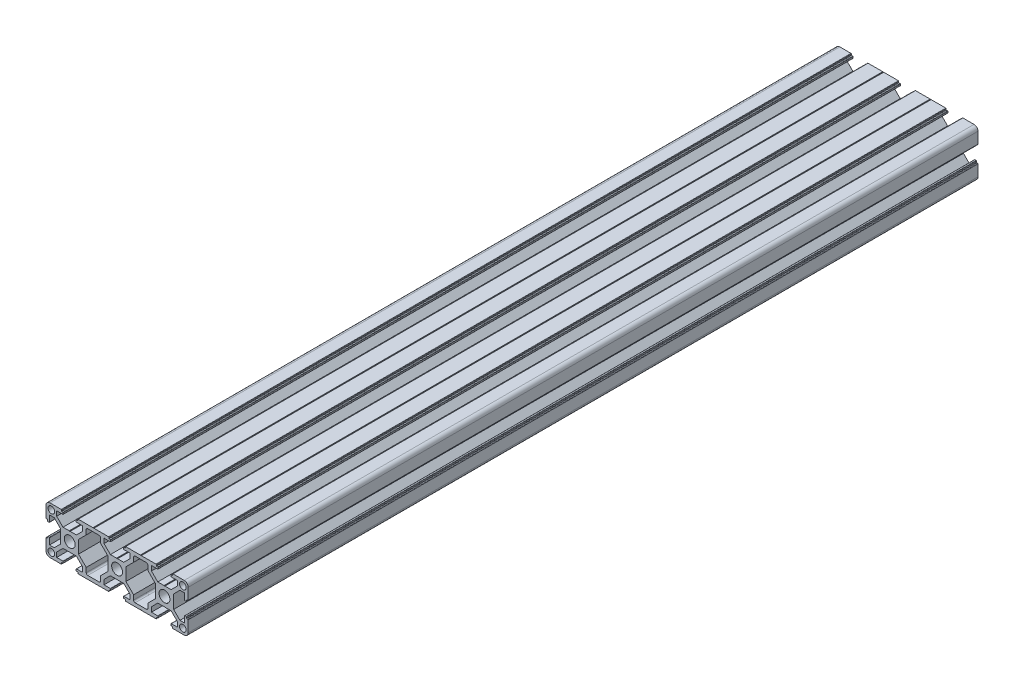
SolidWorks part; units mm, degrees
material "6063-T5"
ref_plane "Спереди" through (0, 0, 0) normal (0, 0, 1) x (1, 0, 0)
ref_plane "Сверху" through (0, 0, 0) normal (0, 1, 0) x (1, 0, 0)
ref_plane "Справа" through (0, 0, 0) normal (1, 0, 0) x (0, 0, -1)
sketch "Эскиз1" plane through (0, 500, 0) normal (0, 0, -1) x (1, 0, 0)
  line L0 (-18.55, 12.8) -> (-11.45, 12.8)
  line L1 (-10.45, 11.8) -> (-10.45, 8.8944)
  line L2 (-10.45, 8.8944) -> (-5.6, 4.0444)
  line L3 (-5.6, 4.0444) -> (-5.6, -4.0444)
  line L4 (-5.6, -4.0444) -> (-10.45, -8.8944)
  line L5 (-10.45, -8.8944) -> (-10.45, -11.8)
  line L6 (-11.45, -12.8) -> (-18.55, -12.8)
  line L7 (-19.55, -11.8) -> (-19.55, -8.8944)
  line L8 (-19.55, -8.8944) -> (-24.4, -4.0444)
  line L9 (-24.4, -4.0444) -> (-24.4, 4.0444)
  line L10 (-24.4, 4.0444) -> (-19.55, 8.8944)
  line L11 (-19.55, 8.8944) -> (-19.55, 11.8)
  line L12 (19.55, 11.8) -> (19.55, 8.8944)
  line L13 (19.55, 8.8944) -> (24.4, 4.0444)
  line L14 (24.4, 4.0444) -> (24.4, -4.0444)
  line L15 (24.4, -4.0444) -> (19.55, -8.8944)
  line L16 (19.55, -8.8944) -> (19.55, -11.8)
  line L17 (18.55, -12.8) -> (11.45, -12.8)
  line L18 (10.45, -11.8) -> (10.45, -8.8944)
  line L19 (10.45, -8.8944) -> (5.6, -4.0444)
  line L20 (5.6, -4.0444) -> (5.6, 4.0444)
  line L21 (5.6, 4.0444) -> (10.45, 8.8944)
  line L22 (10.45, 8.8944) -> (10.45, 11.8)
  line L23 (11.45, 12.8) -> (18.55, 12.8)
  line L24 (15.3377, -15) -> (24.6, -15)
  line L25 (24.8, -14.8) -> (24.8, -14.2)
  line L26 (25, -14) -> (25.7, -14)
  line L27 (25.9, -13.8) -> (25.9, -13)
  line L28 (25.7, -12.8) -> (21.75, -12.8)
  line L29 (21.75, -12.8) -> (21.75, -9.8056)
  line L30 (21.75, -9.8056) -> (25.7556, -5.8)
  line L31 (25.7556, -5.8) -> (29.6623, -5.8)
  line L32 (29.8185, -5.7452) -> (30, -5.6)
  line L33 (30, -5.6) -> (30.1815, -5.7452)
  line L34 (30.3377, -5.8) -> (34.2444, -5.8)
  line L35 (34.2444, -5.8) -> (38.25, -9.8056)
  line L36 (38.25, -9.8056) -> (38.25, -12.8)
  line L37 (38.25, -12.8) -> (34.3, -12.8)
  line L38 (34.1, -13) -> (34.1, -13.8)
  line L39 (34.3, -14) -> (35, -14)
  line L40 (35.2, -14.2) -> (35.2, -14.8)
  line L41 (35.4, -15) -> (42.5, -15)
  line L42 (45, -12.5) -> (45, -5.4)
  line L43 (44.8, -5.2) -> (44.2, -5.2)
  line L44 (44, -5) -> (44, -4.3)
  line L45 (43.8, -4.1) -> (43, -4.1)
  line L46 (42.8, -4.3) -> (42.8, -8.25)
  line L47 (42.8, -8.25) -> (39.8056, -8.25)
  line L48 (39.8056, -8.25) -> (35.8, -4.2444)
  line L49 (35.8, -4.2444) -> (35.8, 4.2444)
  line L50 (35.8, 4.2444) -> (39.8056, 8.25)
  line L51 (39.8056, 8.25) -> (42.8, 8.25)
  line L52 (42.8, 8.25) -> (42.8, 4.3)
  line L53 (43, 4.1) -> (43.8, 4.1)
  line L54 (44, 4.3) -> (44, 5)
  line L55 (44.2, 5.2) -> (44.8, 5.2)
  line L56 (45, 5.4) -> (45, 12.5)
  line L57 (42.5, 15) -> (35.4, 15)
  line L58 (35.2, 14.8) -> (35.2, 14.2)
  line L59 (35, 14) -> (34.3, 14)
  line L60 (34.1, 13.8) -> (34.1, 13)
  line L61 (34.3, 12.8) -> (38.25, 12.8)
  line L62 (38.25, 12.8) -> (38.25, 9.8056)
  line L63 (38.25, 9.8056) -> (34.2444, 5.8)
  line L64 (34.2444, 5.8) -> (30.3377, 5.8)
  line L65 (30.1815, 5.7452) -> (30, 5.6)
  line L66 (30, 5.6) -> (29.8185, 5.7452)
  line L67 (29.6623, 5.8) -> (25.7556, 5.8)
  line L68 (25.7556, 5.8) -> (21.75, 9.8056)
  line L69 (21.75, 9.8056) -> (21.75, 12.8)
  line L70 (21.75, 12.8) -> (25.7, 12.8)
  line L71 (25.9, 13) -> (25.9, 13.8)
  line L72 (25.7, 14) -> (25, 14)
  line L73 (24.8, 14.2) -> (24.8, 14.8)
  line L74 (24.6, 15) -> (15.3377, 15)
  line L75 (15.1815, 14.9452) -> (15, 14.8)
  line L76 (15, 14.8) -> (14.8185, 14.9452)
  line L77 (14.6623, 15) -> (5.4, 15)
  line L78 (5.2, 14.8) -> (5.2, 14.2)
  line L79 (5, 14) -> (4.3, 14)
  line L80 (4.1, 13.8) -> (4.1, 13)
  line L81 (4.3, 12.8) -> (8.25, 12.8)
  line L82 (8.25, 12.8) -> (8.25, 9.8056)
  line L83 (8.25, 9.8056) -> (4.2444, 5.8)
  line L84 (4.2444, 5.8) -> (0.3377, 5.8)
  line L85 (0.1815, 5.7452) -> (0, 5.6)
  line L86 (0, 5.6) -> (-0.1815, 5.7452)
  line L87 (-0.3377, 5.8) -> (-4.2444, 5.8)
  line L88 (-4.2444, 5.8) -> (-8.25, 9.8056)
  line L89 (-8.25, 9.8056) -> (-8.25, 12.8)
  line L90 (-8.25, 12.8) -> (-4.3, 12.8)
  line L91 (-4.1, 13) -> (-4.1, 13.8)
  line L92 (-4.3, 14) -> (-5, 14)
  line L93 (-5.2, 14.2) -> (-5.2, 14.8)
  line L94 (-5.4, 15) -> (-14.6623, 15)
  line L95 (-14.8185, 14.9452) -> (-15, 14.8)
  line L96 (-15, 14.8) -> (-15.1815, 14.9452)
  line L97 (-15.3377, 15) -> (-24.6, 15)
  line L98 (-24.8, 14.8) -> (-24.8, 14.2)
  line L99 (-25, 14) -> (-25.7, 14)
  line L100 (-25.9, 13.8) -> (-25.9, 13)
  line L101 (-25.7, 12.8) -> (-21.75, 12.8)
  line L102 (-21.75, 12.8) -> (-21.75, 9.8056)
  line L103 (-21.75, 9.8056) -> (-25.7556, 5.8)
  line L104 (-25.7556, 5.8) -> (-29.6623, 5.8)
  line L105 (-29.8185, 5.7452) -> (-30, 5.6)
  line L106 (-30, 5.6) -> (-30.1815, 5.7452)
  line L107 (-30.3377, 5.8) -> (-34.2444, 5.8)
  line L108 (-34.2444, 5.8) -> (-38.25, 9.8056)
  line L109 (-38.25, 9.8056) -> (-38.25, 12.8)
  line L110 (-38.25, 12.8) -> (-34.3, 12.8)
  line L111 (-34.1, 13) -> (-34.1, 13.8)
  line L112 (-34.3, 14) -> (-35, 14)
  line L113 (-35.2, 14.2) -> (-35.2, 14.8)
  line L114 (-35.4, 15) -> (-42.5, 15)
  line L115 (-45, 12.5) -> (-45, 5.4)
  line L116 (-44.8, 5.2) -> (-44.2, 5.2)
  line L117 (-44, 5) -> (-44, 4.3)
  line L118 (-43.8, 4.1) -> (-43, 4.1)
  line L119 (-42.8, 4.3) -> (-42.8, 8.25)
  line L120 (-42.8, 8.25) -> (-39.8056, 8.25)
  line L121 (-39.8056, 8.25) -> (-35.8, 4.2444)
  line L122 (-35.8, 4.2444) -> (-35.8, -4.2444)
  line L123 (-35.8, -4.2444) -> (-39.8056, -8.25)
  line L124 (-39.8056, -8.25) -> (-42.8, -8.25)
  line L125 (-42.8, -8.25) -> (-42.8, -4.3)
  line L126 (-43, -4.1) -> (-43.8, -4.1)
  line L127 (-44, -4.3) -> (-44, -5)
  line L128 (-44.2, -5.2) -> (-44.8, -5.2)
  line L129 (-45, -5.4) -> (-45, -12.5)
  line L130 (-42.5, -15) -> (-35.4, -15)
  line L131 (-35.2, -14.8) -> (-35.2, -14.2)
  line L132 (-35, -14) -> (-34.3, -14)
  line L133 (-34.1, -13.8) -> (-34.1, -13)
  line L134 (-34.3, -12.8) -> (-38.25, -12.8)
  line L135 (-38.25, -12.8) -> (-38.25, -9.8056)
  line L136 (-38.25, -9.8056) -> (-34.2444, -5.8)
  line L137 (-34.2444, -5.8) -> (-30.3377, -5.8)
  line L138 (-30.1815, -5.7452) -> (-30, -5.6)
  line L139 (-30, -5.6) -> (-29.8185, -5.7452)
  line L140 (-29.6623, -5.8) -> (-25.7556, -5.8)
  line L141 (-25.7556, -5.8) -> (-21.75, -9.8056)
  line L142 (-21.75, -9.8056) -> (-21.75, -12.8)
  line L143 (-21.75, -12.8) -> (-25.7, -12.8)
  line L144 (-25.9, -13) -> (-25.9, -13.8)
  line L145 (-25.7, -14) -> (-25, -14)
  line L146 (-24.8, -14.2) -> (-24.8, -14.8)
  line L147 (-24.6, -15) -> (-15.3377, -15)
  line L148 (-15.1815, -14.9452) -> (-15, -14.8)
  line L149 (-15, -14.8) -> (-14.8185, -14.9452)
  line L150 (-14.6623, -15) -> (-5.4, -15)
  line L151 (-5.2, -14.8) -> (-5.2, -14.2)
  line L152 (-5, -14) -> (-4.3, -14)
  line L153 (-4.1, -13.8) -> (-4.1, -13)
  line L154 (-4.3, -12.8) -> (-8.25, -12.8)
  line L155 (-8.25, -12.8) -> (-8.25, -9.8056)
  line L156 (-8.25, -9.8056) -> (-4.2444, -5.8)
  line L157 (-4.2444, -5.8) -> (-0.3377, -5.8)
  line L158 (-0.1815, -5.7452) -> (0, -5.6)
  line L159 (0, -5.6) -> (0.1815, -5.7452)
  line L160 (0.3377, -5.8) -> (4.2444, -5.8)
  line L161 (4.2444, -5.8) -> (8.25, -9.8056)
  line L162 (8.25, -9.8056) -> (8.25, -12.8)
  line L163 (8.25, -12.8) -> (4.3, -12.8)
  line L164 (4.1, -13) -> (4.1, -13.8)
  line L165 (4.3, -14) -> (5, -14)
  line L166 (5.2, -14.2) -> (5.2, -14.8)
  line L167 (5.4, -15) -> (14.6623, -15)
  line L168 (14.8185, -14.9452) -> (15, -14.8)
  line L169 (15, -14.8) -> (15.1815, -14.9452)
  circle A0 centre (41.625, -11.625) radius 2.1
  circle A1 centre (41.625, 11.625) radius 2.1
  circle A2 centre (-41.625, 11.625) radius 2.1
  circle A3 centre (-41.625, -11.625) radius 2.1
  circle A4 centre (30, 0) radius 3.45
  circle A5 centre (-30, 0) radius 3.45
  circle A6 centre (0, 0) radius 3.45
  arc A7 (-11.45, 12.8) -> (-10.45, 11.8) centre (-11.45, 11.8) cw
  arc A8 (-10.45, -11.8) -> (-11.45, -12.8) centre (-11.45, -11.8) cw
  arc A9 (-18.55, -12.8) -> (-19.55, -11.8) centre (-18.55, -11.8) cw
  arc A10 (-19.55, 11.8) -> (-18.55, 12.8) centre (-18.55, 11.8) cw
  arc A11 (19.55, -11.8) -> (18.55, -12.8) centre (18.55, -11.8) cw
  arc A12 (11.45, -12.8) -> (10.45, -11.8) centre (11.45, -11.8) cw
  arc A13 (10.45, 11.8) -> (11.45, 12.8) centre (11.45, 11.8) cw
  arc A14 (18.55, 12.8) -> (19.55, 11.8) centre (18.55, 11.8) cw
  arc A15 (24.6, -15) -> (24.8, -14.8) centre (24.6, -14.8) ccw
  arc A16 (24.8, -14.2) -> (25, -14) centre (25, -14.2) cw
  arc A17 (25.7, -14) -> (25.9, -13.8) centre (25.7, -13.8) ccw
  arc A18 (25.9, -13) -> (25.7, -12.8) centre (25.7, -13) ccw
  arc A19 (29.6623, -5.8) -> (29.8185, -5.7452) centre (29.6623, -5.55) ccw
  arc A20 (30.1815, -5.7452) -> (30.3377, -5.8) centre (30.3377, -5.55) ccw
  arc A21 (34.3, -12.8) -> (34.1, -13) centre (34.3, -13) ccw
  arc A22 (34.1, -13.8) -> (34.3, -14) centre (34.3, -13.8) ccw
  arc A23 (35, -14) -> (35.2, -14.2) centre (35, -14.2) cw
  arc A24 (35.2, -14.8) -> (35.4, -15) centre (35.4, -14.8) ccw
  arc A25 (42.5, -15) -> (45, -12.5) centre (42.5, -12.5) ccw
  arc A26 (45, -5.4) -> (44.8, -5.2) centre (44.8, -5.4) ccw
  arc A27 (44.2, -5.2) -> (44, -5) centre (44.2, -5) cw
  arc A28 (44, -4.3) -> (43.8, -4.1) centre (43.8, -4.3) ccw
  arc A29 (43, -4.1) -> (42.8, -4.3) centre (43, -4.3) ccw
  arc A30 (42.8, 4.3) -> (43, 4.1) centre (43, 4.3) ccw
  arc A31 (43.8, 4.1) -> (44, 4.3) centre (43.8, 4.3) ccw
  arc A32 (44, 5) -> (44.2, 5.2) centre (44.2, 5) cw
  arc A33 (44.8, 5.2) -> (45, 5.4) centre (44.8, 5.4) ccw
  arc A34 (45, 12.5) -> (42.5, 15) centre (42.5, 12.5) ccw
  arc A35 (35.4, 15) -> (35.2, 14.8) centre (35.4, 14.8) ccw
  arc A36 (35.2, 14.2) -> (35, 14) centre (35, 14.2) cw
  arc A37 (34.3, 14) -> (34.1, 13.8) centre (34.3, 13.8) ccw
  arc A38 (34.1, 13) -> (34.3, 12.8) centre (34.3, 13) ccw
  arc A39 (30.3377, 5.8) -> (30.1815, 5.7452) centre (30.3377, 5.55) ccw
  arc A40 (29.8185, 5.7452) -> (29.6623, 5.8) centre (29.6623, 5.55) ccw
  arc A41 (25.7, 12.8) -> (25.9, 13) centre (25.7, 13) ccw
  arc A42 (25.9, 13.8) -> (25.7, 14) centre (25.7, 13.8) ccw
  arc A43 (25, 14) -> (24.8, 14.2) centre (25, 14.2) cw
  arc A44 (24.8, 14.8) -> (24.6, 15) centre (24.6, 14.8) ccw
  arc A45 (15.3377, 15) -> (15.1815, 14.9452) centre (15.3377, 14.75) ccw
  arc A46 (14.8185, 14.9452) -> (14.6623, 15) centre (14.6623, 14.75) ccw
  arc A47 (5.4, 15) -> (5.2, 14.8) centre (5.4, 14.8) ccw
  arc A48 (5.2, 14.2) -> (5, 14) centre (5, 14.2) cw
  arc A49 (4.3, 14) -> (4.1, 13.8) centre (4.3, 13.8) ccw
  arc A50 (4.1, 13) -> (4.3, 12.8) centre (4.3, 13) ccw
  arc A51 (0.3377, 5.8) -> (0.1815, 5.7452) centre (0.3377, 5.55) ccw
  arc A52 (-0.1815, 5.7452) -> (-0.3377, 5.8) centre (-0.3377, 5.55) ccw
  arc A53 (-4.3, 12.8) -> (-4.1, 13) centre (-4.3, 13) ccw
  arc A54 (-4.1, 13.8) -> (-4.3, 14) centre (-4.3, 13.8) ccw
  arc A55 (-5, 14) -> (-5.2, 14.2) centre (-5, 14.2) cw
  arc A56 (-5.2, 14.8) -> (-5.4, 15) centre (-5.4, 14.8) ccw
  arc A57 (-14.6623, 15) -> (-14.8185, 14.9452) centre (-14.6623, 14.75) ccw
  arc A58 (-15.1815, 14.9452) -> (-15.3377, 15) centre (-15.3377, 14.75) ccw
  arc A59 (-24.6, 15) -> (-24.8, 14.8) centre (-24.6, 14.8) ccw
  arc A60 (-24.8, 14.2) -> (-25, 14) centre (-25, 14.2) cw
  arc A61 (-25.7, 14) -> (-25.9, 13.8) centre (-25.7, 13.8) ccw
  arc A62 (-25.9, 13) -> (-25.7, 12.8) centre (-25.7, 13) ccw
  arc A63 (-29.6623, 5.8) -> (-29.8185, 5.7452) centre (-29.6623, 5.55) ccw
  arc A64 (-30.1815, 5.7452) -> (-30.3377, 5.8) centre (-30.3377, 5.55) ccw
  arc A65 (-34.3, 12.8) -> (-34.1, 13) centre (-34.3, 13) ccw
  arc A66 (-34.1, 13.8) -> (-34.3, 14) centre (-34.3, 13.8) ccw
  arc A67 (-35, 14) -> (-35.2, 14.2) centre (-35, 14.2) cw
  arc A68 (-35.2, 14.8) -> (-35.4, 15) centre (-35.4, 14.8) ccw
  arc A69 (-42.5, 15) -> (-45, 12.5) centre (-42.5, 12.5) ccw
  arc A70 (-45, 5.4) -> (-44.8, 5.2) centre (-44.8, 5.4) ccw
  arc A71 (-44.2, 5.2) -> (-44, 5) centre (-44.2, 5) cw
  arc A72 (-44, 4.3) -> (-43.8, 4.1) centre (-43.8, 4.3) ccw
  arc A73 (-43, 4.1) -> (-42.8, 4.3) centre (-43, 4.3) ccw
  arc A74 (-42.8, -4.3) -> (-43, -4.1) centre (-43, -4.3) ccw
  arc A75 (-43.8, -4.1) -> (-44, -4.3) centre (-43.8, -4.3) ccw
  arc A76 (-44, -5) -> (-44.2, -5.2) centre (-44.2, -5) cw
  arc A77 (-44.8, -5.2) -> (-45, -5.4) centre (-44.8, -5.4) ccw
  arc A78 (-45, -12.5) -> (-42.5, -15) centre (-42.5, -12.5) ccw
  arc A79 (-35.4, -15) -> (-35.2, -14.8) centre (-35.4, -14.8) ccw
  arc A80 (-35.2, -14.2) -> (-35, -14) centre (-35, -14.2) cw
  arc A81 (-34.3, -14) -> (-34.1, -13.8) centre (-34.3, -13.8) ccw
  arc A82 (-34.1, -13) -> (-34.3, -12.8) centre (-34.3, -13) ccw
  arc A83 (-30.3377, -5.8) -> (-30.1815, -5.7452) centre (-30.3377, -5.55) ccw
  arc A84 (-29.8185, -5.7452) -> (-29.6623, -5.8) centre (-29.6623, -5.55) ccw
  arc A85 (-25.7, -12.8) -> (-25.9, -13) centre (-25.7, -13) ccw
  arc A86 (-25.9, -13.8) -> (-25.7, -14) centre (-25.7, -13.8) ccw
  arc A87 (-25, -14) -> (-24.8, -14.2) centre (-25, -14.2) cw
  arc A88 (-24.8, -14.8) -> (-24.6, -15) centre (-24.6, -14.8) ccw
  arc A89 (-15.3377, -15) -> (-15.1815, -14.9452) centre (-15.3377, -14.75) ccw
  arc A90 (-14.8185, -14.9452) -> (-14.6623, -15) centre (-14.6623, -14.75) ccw
  arc A91 (-5.4, -15) -> (-5.2, -14.8) centre (-5.4, -14.8) ccw
  arc A92 (-5.2, -14.2) -> (-5, -14) centre (-5, -14.2) cw
  arc A93 (-4.3, -14) -> (-4.1, -13.8) centre (-4.3, -13.8) ccw
  arc A94 (-4.1, -13) -> (-4.3, -12.8) centre (-4.3, -13) ccw
  arc A95 (-0.3377, -5.8) -> (-0.1815, -5.7452) centre (-0.3377, -5.55) ccw
  arc A96 (0.1815, -5.7452) -> (0.3377, -5.8) centre (0.3377, -5.55) ccw
  arc A97 (4.3, -12.8) -> (4.1, -13) centre (4.3, -13) ccw
  arc A98 (4.1, -13.8) -> (4.3, -14) centre (4.3, -13.8) ccw
  arc A99 (5, -14) -> (5.2, -14.2) centre (5, -14.2) cw
  arc A100 (5.2, -14.8) -> (5.4, -15) centre (5.4, -14.8) ccw
  arc A101 (14.6623, -15) -> (14.8185, -14.9452) centre (14.6623, -14.75) ccw
  arc A102 (15.1815, -14.9452) -> (15.3377, -15) centre (15.3377, -14.75) ccw
extrude "Бобышка-Вытянуть1" add sketch "Эскиз1" against normal blind 500
